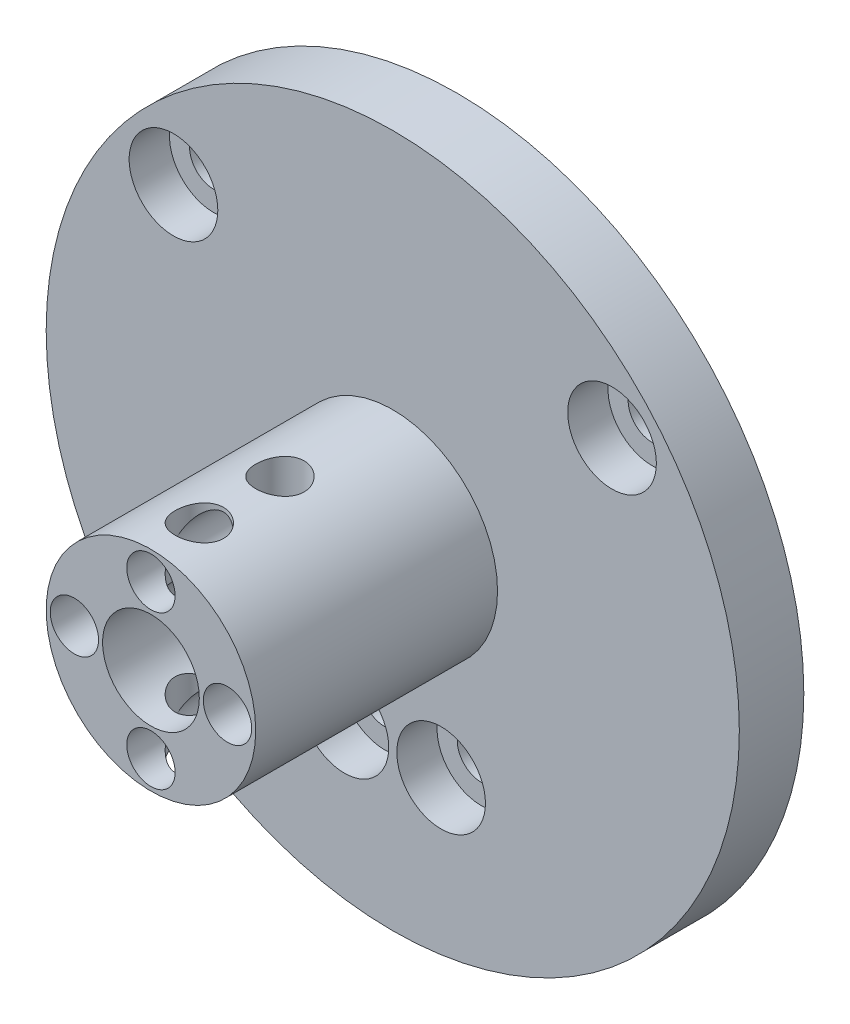
SolidWorks part; units mm, degrees
ref_plane "Front Plane" through (0, 0, 0) normal (0, 0, 1) x (1, 0, 0)
ref_plane "Top Plane" through (0, 0, 0) normal (0, 1, 0) x (1, 0, 0)
ref_plane "Right Plane" through (0, 0, 0) normal (1, 0, 0) x (0, 0, -1)
sketch "Sketch2" plane through (0, 0, 0) normal (0, 0, 1) x (1, 0, 0)
  circle A0 centre (-8.896, 29.0609) radius 1.5
  circle A1 centre (18.3098, 29.0609) radius 1.5
  circle A2 centre (1.7069, 5.5) radius 1.5
  circle A3 centre (7.7069, 5.5) radius 1.5
  circle A4 centre (4.7069, 17.2804) radius 21.5
  dimension "D1" = 23.5609
  dimension "D2" = 3
  dimension "D3" = 3
  dimension "D5" = 27.2058
  dimension "D6" = 6
  dimension "D7" = 3
  dimension "D8" = 3
  dimension "D10" = 3
  dimension "D4" = 23.5609
  dimension "D11" = 43
  dimension "D9" = 11.7804
extrude "Boss-Extrude1" add sketch "Sketch2" along normal blind 4
sketch "Sketch4" plane through (0, 0, 4) normal (0, 0, 1) x (1, 0, 0)
  circle A0 centre (-8.896, 29.0609) radius 2.75
  circle A1 centre (18.3098, 29.0609) radius 2.75
  circle A2 centre (7.7069, 5.5) radius 2.75
  circle A3 centre (1.7069, 5.5) radius 2.75
  dimension "D1" = 5.5
  dimension "D2" = 5.5
  dimension "D3" = 5.5
  dimension "D4" = 5.5
extrude "Cut-Extrude1" cut sketch "Sketch4" against normal blind 2.5
sketch "Sketch6" plane through (0, 0, 4) normal (0, 0, 1) x (1, 0, 0)
  circle A0 centre (4.7069, 17.2804) radius 6.5
  dimension "D1" = 13
extrude "Boss-Extrude2" add sketch "Sketch6" along normal blind 15
sketch "Sketch8" plane through (0, 0, 19) normal (0, 0, 1) x (1, 0, 0)
  circle A0 centre (4.7069, 17.2804) radius 3
  dimension "D1" = 6
extrude "Cut-Extrude2" cut sketch "Sketch8" against normal blind 61
sketch "Sketch9" plane through (0, 0, 19) normal (0, 0, 1) x (1, 0, 0)
  circle A0 centre (4.7069, 17.2804) radius 4.75 construction
  circle A1 centre (4.7069, 22.0304) radius 1.5
  circle A2 centre (9.4569, 17.2804) radius 1.5
  circle A3 centre (4.7069, 12.5304) radius 1.5
  circle A4 centre (-0.0431, 17.2804) radius 1.5
  dimension "D1" = 9.5
  dimension "D2" = 3
  dimension "D3" = 3
  dimension "D4" = 3
  dimension "D5" = 3
extrude "Cut-Extrude3" cut sketch "Sketch9" against normal blind 8
sketch "Sketch11" plane through (0, 0, 0) normal (0, 1, 0) x (1, 0, 0)
  line L0 (-1.7931, -19) -> (11.2069, -19) construction
  circle A0 centre (4.7069, -16) radius 1.5
  circle A1 centre (4.7069, -11) radius 1.5
  dimension "D1" = 3
  dimension "D2" = 3
  dimension "D3" = 5
  dimension "D4" = 3
extrude "Cut-Extrude5" cut sketch "Sketch11" along normal blind 29.0648
sketch "Sketch13" plane through (0, 0, 0) normal (0, 0, -1) x (-1, 0, 0)
  line L0 (-18.3098, 29.0609) -> (-4.7069, 17.2804) construction
  line L1 (-4.7069, 17.2804) -> (8.896, 29.0609) construction
  line L2 (-7.7069, 5.5) -> (-4.7069, 17.2804) construction
  line L3 (-4.7069, 17.2804) -> (-1.7069, 5.5) construction
  circle A0 centre (-4.7069, 17.2804) radius 6.5 construction
  dimension "D1" = 17.9949
  dimension "D2" = 12.1564
  dimension "D3" = 17.9949
  dimension "D4" = 12.1564
